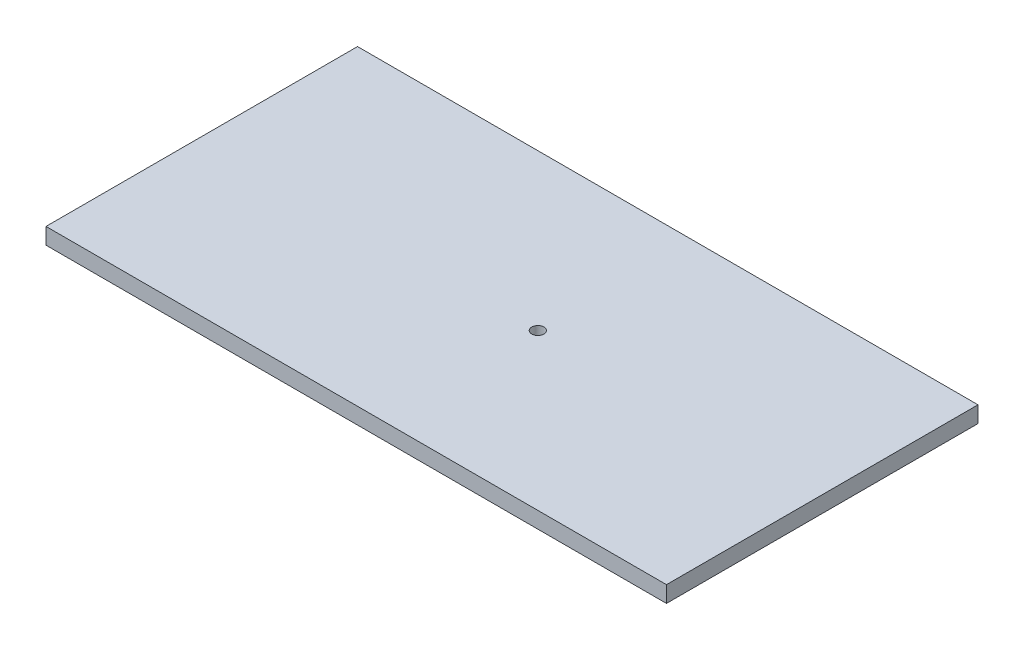
SolidWorks part; units mm, degrees
ref_plane "Front Plane" through (0, 0, 0) normal (0, 0, 1) x (1, 0, 0)
ref_plane "Top Plane" through (0, 0, 0) normal (0, 1, 0) x (1, 0, 0)
ref_plane "Right Plane" through (0, 0, 0) normal (1, 0, 0) x (0, 0, -1)
sketch "Sketch1" plane through (0, 0, 0) normal (0, 1, 0) x (1, 0, 0)
  line L1 (-30.48, 15.3035) -> (30.48, 15.3035)
  line L2 (-30.48, 15.3035) -> (-30.48, -15.3035)
  line L3 (-30.48, -15.3035) -> (30.48, -15.3035)
  line L4 (30.48, 15.3035) -> (30.48, -15.3035)
  circle A0 centre (2.54, 0) radius 0.6
  dimension "D7" = 1.2
  dimension "D1" = 60.96
  dimension "D2" = 30.48
  dimension "D3" = 30.607
  dimension "D4" = 15.3035
  dimension "D5" = 27.94
  dimension "D6" = 15.3035
extrude "Boss-Extrude2" add sketch "Sketch1" along normal blind 1.6
